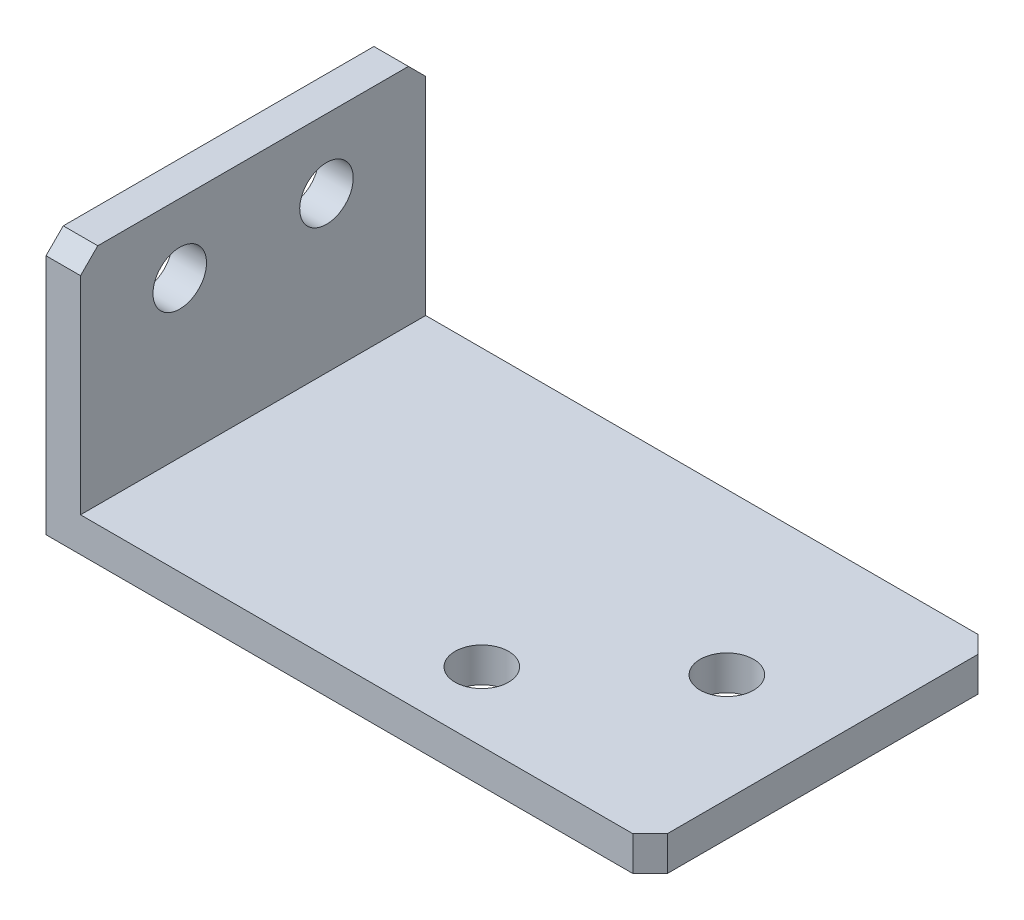
SolidWorks part; units mm, degrees
material "6063-T5"
ref_plane "Спереди" through (0, 0, 0) normal (0, 0, 1) x (1, 0, 0)
ref_plane "Сверху" through (0, 0, 0) normal (0, 1, 0) x (1, 0, 0)
ref_plane "Справа" through (0, 0, 0) normal (1, 0, 0) x (0, 0, -1)
sketch "Sketch1" plane through (0, 0, 0) normal (0, 0, 1) x (1, 0, 0)
  line L0 (0, 0) -> (35, 0)
  line L1 (35, 0) -> (35, 2)
  line L2 (35, 2) -> (2, 2)
  line L3 (2, 2) -> (2, 15)
  line L4 (2, 15) -> (0, 15)
  line L5 (0, 15) -> (0, 0)
  dimension "D1" = 35
  dimension "D2" = 15
  dimension "D3" = 2
  dimension "D4" = 2
extrude "Boss-Extrude1" add sketch "Sketch1" along normal blind 20
sketch "Sketch2" plane through (0, 0, 0) normal (-1, 0, 0) x (0, 0, 1)
  line L2 (20, 0) -> (0, 0) construction
  line L3 (10, 0) -> (10, 14.2922) construction
  circle A0 centre (14.25, 11) radius 1.55
  circle A1 centre (5.75, 11) radius 1.55
  dimension "D5" = 3.1
  dimension "D1" = 8.5
  dimension "D3" = 11
extrude "Cut-Extrude1" cut sketch "Sketch2" against normal up to surface (2 mm away) up to face at (2, 8.5, 10)
sketch "Sketch5" plane through (0, 2, 0) normal (0, 1, 0) x (1, 0, 0)
  line L0 (0, -20) -> (0, 0) construction
  line L2 (35, -20) -> (2, -20) construction
  circle A0 centre (21.25, -16) radius 1.55
  circle A1 centre (28.75, -9.3) radius 1.55
  dimension "D3" = 3.1
  dimension "D1" = 4
  dimension "D2" = 6.7
  dimension "D4" = 7.5
  dimension "D5" = 21.25
extrude "Cut-Extrude4" cut sketch "Sketch5" against normal through all
chamfer "Chamfer1" distance 1 angle 45 4 edges at (35, 1, 0) (1, 15, 0) (1, 15, 20) (35, 1, 20)
